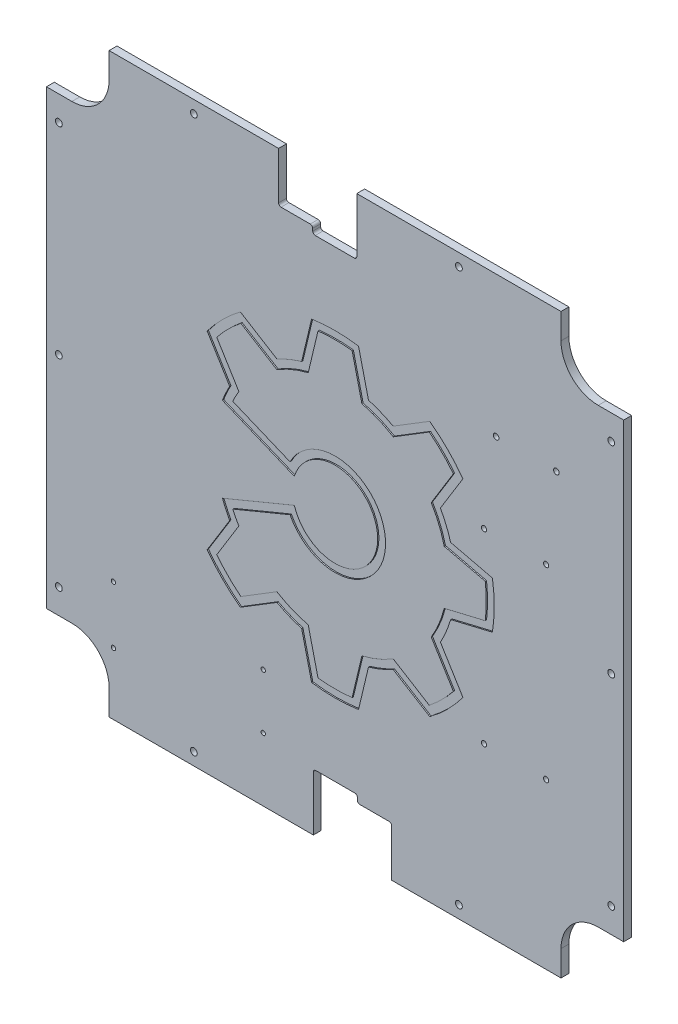
SolidWorks part; units mm, degrees
material "Acrylic (Medium-high impact)"
ref_plane "Front Plane" through (0, 0, 0) normal (0, 0, 1) x (1, 0, 0)
ref_plane "Top Plane" through (0, 0, 0) normal (0, 1, 0) x (1, 0, 0)
ref_plane "Right Plane" through (0, 0, 0) normal (1, 0, 0) x (0, 0, -1)
sketch "Sketch1" plane through (0, 0, 0) normal (0, 0, 1) x (1, 0, 0)
  line L0 (182, -212) -> (212, -212)
  line L1 (-182, -232.5) -> (-17.5, -232.5)
  line L2 (-232.5, -182) -> (-232.5, 0)
  line L3 (212, -212) -> (212, -182)
  line L4 (232.5, -182) -> (232.5, 0)
  line L5 (45.5, -232.5) -> (182, -232.5)
  line L6 (-232.5, 0) -> (232.5, 0) construction
  line L7 (-182, -212) -> (-212, -212)
  line L8 (-212, -212) -> (-212, -182)
  line L9 (232.5, 182) -> (232.5, 0)
  line L10 (232.5, 182) -> (212, 182)
  line L11 (212, 212) -> (212, 182)
  line L12 (182, 212) -> (212, 212)
  line L13 (182, 232.5) -> (182, 212)
  line L14 (182, 232.5) -> (17.5, 232.5)
  line L15 (17.5, 232.5) -> (17.5, 186.5)
  line L16 (-45.5, 186.5) -> (17.5, 186.5)
  line L17 (-45.5, 232.5) -> (-45.5, 186.5)
  line L18 (-45.5, 232.5) -> (-182, 232.5)
  line L19 (-182, 232.5) -> (-182, 212)
  line L20 (-182, 212) -> (-212, 212)
  line L21 (232.5, -182) -> (212, -182)
  line L22 (182, -232.5) -> (182, -212)
  line L23 (-212, 212) -> (-212, 182)
  line L24 (45.5, -232.5) -> (45.5, -186.5)
  line L25 (45.5, -186.5) -> (-17.5, -186.5)
  line L26 (-17.5, -232.5) -> (-17.5, -186.5)
  line L27 (-232.5, 182) -> (-212, 182)
  line L28 (-232.5, 182) -> (-232.5, 0)
  line L29 (-232.5, -182) -> (-212, -182)
  line L30 (-182, -232.5) -> (-182, -212)
  line L31 (0, 0) -> (0, -232.5) construction
  line L32 (-116.5, 222.5) -> (102.5, 222.5) construction
  circle A0 centre (-222.5, -162) radius 2.75
  circle A1 centre (222.5, -162) radius 2.75
  circle A2 centre (222.5, 162) radius 2.75
  circle A3 centre (-222.5, 162) radius 2.75
  circle A4 centre (-222.5, 0) radius 2.75
  circle A5 centre (222.5, 0) radius 2.75
  circle A6 centre (-113.75, 222.5) radius 2.75
  circle A7 centre (99.75, 222.5) radius 2.75
  circle A8 centre (99.75, -222.5) radius 2.75
  circle A9 centre (-113.75, -222.5) radius 2.75
  point P0 (0, 0)
  point P3 (0, 0)
  point P38 (0, 0)
  point P40 (14, -186.5)
  point P55 (-113.75, 232.5)
  point P56 (99.75, 232.5)
  point P68 (0, 0)
  dimension "D21" = 20.5
  dimension "D22" = 20.5
  dimension "D23" = 232.5
  dimension "D7" = 5.5
  dimension "D8" = 10
  dimension "D9" = 20
  dimension "D13" = 10
  dimension "D3" = 50.5
  dimension "D4" = 20.5
  dimension "D5" = 20.5
  dimension "D6" = 2
  dimension "D10" = 14
  dimension "D11" = 50.5
  dimension "D12" = 50.5
  dimension "D15" = 63
  dimension "D16" = 46
  dimension "D18" = 50.5
  dimension "D20" = 465
extrude "Boss-Extrude1" add sketch "Sketch1" along normal blind 6.35
sketch "Sketch4" plane through (0, 0, 6.35) normal (0, 0, 1) x (1, 0, 0)
  line L1 (45.5, -186.5) -> (18, -186.5)
  line L2 (45.5, -186.5) -> (45.5, -192.5)
  line L3 (45.5, -192.5) -> (18, -192.5)
  line L4 (18, -186.5) -> (18, -192.5)
  line L5 (-45.5, 186.5) -> (-18, 186.5)
  line L6 (-45.5, 186.5) -> (-45.5, 192.5)
  line L7 (-45.5, 192.5) -> (-18, 192.5)
  line L8 (-18, 186.5) -> (-18, 192.5)
  dimension "D1" = 27.5
  dimension "D2" = 6
extrude "Boss-Extrude2" add sketch "Sketch4" against normal up to surface (6.35 mm away) up to face at (0, 0, 0)
sketch "Sketch2" plane through (0, 0, 6.35) normal (0, 0, 1) x (1, 0, 0)
  line L0 (232.5, 182) -> (212, 182) construction
  line L1 (212, 212) -> (182, 212) construction
  line L2 (212, 182) -> (212, 212) construction
  line L3 (212, 212) -> (182, 212)
  line L4 (212, 182) -> (212, 212)
  line L5 (182, -212) -> (212, -212) construction
  line L6 (212, -212) -> (212, -182) construction
  line L7 (182, -212) -> (212, -212)
  line L8 (212, -212) -> (212, -182)
  line L9 (-212, -212) -> (-182, -212) construction
  line L10 (-212, -182) -> (-212, -212) construction
  line L11 (-212, 212) -> (-212, 182) construction
  line L12 (-182, 212) -> (-212, 212) construction
  line L13 (-212, -212) -> (-182, -212)
  line L14 (-212, -182) -> (-212, -212)
  line L15 (-212, 212) -> (-212, 182)
  line L16 (-182, 212) -> (-212, 212)
  arc A0 (182, 212) -> (212, 182) centre (212, 212) ccw
  arc A1 (212, -182) -> (182, -212) centre (212, -212) ccw
  arc A2 (-212, 182) -> (-182, 212) centre (-212, 212) ccw
  arc A3 (-182, -212) -> (-212, -182) centre (-212, -212) ccw
extrude "Cut-Extrude1" cut sketch "Sketch2" against normal up to surface (6.35 mm away) contours A0 L4 L3
sketch "Sketch3" plane through (0, 0, 6.35) normal (0, 0, 1) x (1, 0, 0)
  line L0 (0, 0) -> (125, 0) construction
  line L1 (0, 0) -> (123.9306, -16.3158) construction
  line L2 (0, 0) -> (115.4849, -47.8354) construction
  line L3 (0, 0) -> (120.7407, -32.3524) construction
  line L4 (123.9306, -16.3158) -> (90.5555, -24.2643) construction
  line L5 (123.9306, 16.3158) -> (90.5555, 24.2643) construction
  line L6 (76.0952, -99.1692) -> (46.875, -81.1899) construction
  line L7 (99.1692, -76.0952) -> (81.1899, -46.875) construction
  line L8 (-16.3158, -123.9306) -> (-24.2643, -90.5555) construction
  line L9 (16.3158, -123.9306) -> (24.2643, -90.5555) construction
  line L10 (-99.1692, -76.0952) -> (-81.1899, -46.875) construction
  line L11 (-76.0952, -99.1692) -> (-46.875, -81.1899) construction
  line L12 (-82.4139, 37.5736) -> (-36.2491, 18.4515)
  line L13 (-95.3084, 75.8792) -> (-77.4822, 46.9078)
  line L14 (-76.0952, 99.1692) -> (-46.875, 81.1899) construction
  line L15 (-99.1692, 76.0952) -> (-81.1899, 46.875) construction
  line L16 (16.3158, 123.9306) -> (24.2643, 90.5555) construction
  line L17 (-16.3158, 123.9306) -> (-24.2643, 90.5555) construction
  line L18 (99.1692, 76.0952) -> (81.1899, 46.875) construction
  line L19 (76.0952, 99.1692) -> (46.875, 81.1899) construction
  line L20 (0, 0) -> (88.3883, -88.3883) construction
  line L21 (0, 0) -> (0, -125) construction
  line L22 (0, 0) -> (-88.3883, -88.3883) construction
  line L23 (0, 0) -> (-125, 0) construction
  line L24 (0, 0) -> (-88.3883, 88.3883) construction
  line L25 (0, 0) -> (0, 125) construction
  line L26 (0, 0) -> (88.3883, 88.3883) construction
  line L27 (-86.6137, 35.8766) -> (-34.6455, 14.3506) construction
  line L28 (-86.6137, -35.8766) -> (-34.6455, -14.3506) construction
  line L29 (-75.8792, 95.3084) -> (-46.9078, 77.4822)
  line L30 (-123.9306, 16.3158) -> (-90.5555, 24.2643) [skipped]
  line L31 (-123.9306, -16.3158) -> (-90.5555, -24.2643) [skipped]
  line L32 (-13.7385, 121.0479) -> (-21.6193, 87.957)
  line L33 (13.7385, 121.0479) -> (21.6193, 87.957)
  line L34 (75.8792, 95.3084) -> (46.9078, 77.4822)
  line L35 (95.3084, 75.8792) -> (77.4822, 46.9078)
  line L36 (121.0479, 13.7385) -> (87.957, 21.6193)
  line L37 (121.0479, -13.7385) -> (87.957, -21.6193)
  line L38 (95.3084, -75.8792) -> (77.4822, -46.9078)
  line L39 (75.8792, -95.3084) -> (46.9078, -77.4822)
  line L40 (13.7385, -121.0479) -> (21.6193, -87.957)
  line L41 (-13.7385, -121.0479) -> (-21.6193, -87.957)
  line L42 (-75.8792, -95.3084) -> (-46.9078, -77.4822)
  line L43 (-95.3084, -75.8792) -> (-77.4822, -46.9078)
  line L44 (-82.4139, -37.5736) -> (-36.2491, -18.4515)
  line L45 (-90.714, 34.1384) -> (-32.7912, 10.146)
  line L46 (-103.0085, 76.2763) -> (-84.8748, 46.8052)
  line L47 (-76.2763, 103.0085) -> (-46.8052, 84.8748)
  line L48 (-18.9025, 126.7735) -> (-26.9193, 93.1118)
  line L49 (18.9025, 126.7735) -> (26.9193, 93.1118)
  line L50 (76.2763, 103.0085) -> (46.8052, 84.8748)
  line L51 (103.0085, 76.2763) -> (84.8748, 46.8052)
  line L52 (126.7735, 18.9025) -> (93.1118, 26.9193)
  line L53 (126.7735, -18.9025) -> (93.1118, -26.9193)
  line L54 (103.0085, -76.2763) -> (84.8748, -46.8052)
  line L55 (76.2763, -103.0085) -> (46.8052, -84.8748)
  line L56 (18.9025, -126.7735) -> (26.9193, -93.1118)
  line L57 (-18.9025, -126.7735) -> (-26.9193, -93.1118)
  line L58 (-76.2763, -103.0085) -> (-46.8052, -84.8748)
  line L59 (-103.0085, -76.2763) -> (-84.8748, -46.8052)
  line L60 (-90.714, -34.1384) -> (-32.7912, -10.146)
  line L61 (55, 0) -> (-55, 0) construction
  arc A0 (-34.6455, -14.3506) -> (-34.6455, 14.3506) centre (0, 0) ccw construction
  arc A1 (99.1692, 76.0952) -> (76.0952, 99.1692) centre (0, 0) ccw construction
  arc A2 (-36.2491, -18.4515) -> (-36.2491, 18.4515) centre (0, 0) ccw
  arc A3 (90.5555, 24.2643) -> (81.1899, 46.875) centre (0, 0) ccw construction
  arc A4 (81.1899, -46.875) -> (90.5555, -24.2643) centre (0, 0) ccw construction
  arc A5 (24.2643, -90.5555) -> (46.875, -81.1899) centre (0, 0) ccw construction
  arc A6 (-46.875, -81.1899) -> (-24.2643, -90.5555) centre (0, 0) ccw construction
  arc A7 (-86.6137, -35.8766) -> (-81.1899, -46.875) centre (0, 0) ccw construction
  arc A8 (-81.1899, 46.875) -> (-86.6137, 35.8766) centre (0, 0) ccw construction
  arc A9 (-24.2643, 90.5555) -> (-46.875, 81.1899) centre (0, 0) ccw construction
  arc A10 (46.875, 81.1899) -> (24.2643, 90.5555) centre (0, 0) ccw construction
  arc A11 (115.4849, -47.8354) -> (120.7407, -32.3524) centre (0, 0) ccw construction
  arc A12 (123.9306, -16.3158) -> (123.9306, 16.3158) centre (0, 0) ccw construction
  arc A13 (76.0952, -99.1692) -> (99.1692, -76.0952) centre (0, 0) ccw construction
  arc A14 (-16.3158, -123.9306) -> (16.3158, -123.9306) centre (0, 0) ccw construction
  arc A15 (-99.1692, -76.0952) -> (-76.0952, -99.1692) centre (0, 0) ccw construction
  arc A16 (-77.4822, 46.9078) -> (-82.4139, 37.5736) centre (0, 0) ccw
  arc A17 (-76.0952, 99.1692) -> (-99.1692, 76.0952) centre (0, 0) ccw construction
  arc A18 (16.3158, 123.9306) -> (-16.3158, 123.9306) centre (0, 0) ccw construction
  arc A19 (-75.8792, 95.3084) -> (-95.3084, 75.8792) centre (0, 0) ccw
  arc A20 (-21.6193, 87.957) -> (-46.9078, 77.4822) centre (0, 0) ccw
  arc A21 (13.7385, 121.0479) -> (-13.7385, 121.0479) centre (0, 0) ccw
  arc A22 (46.9078, 77.4822) -> (21.6193, 87.957) centre (0, 0) ccw
  arc A23 (95.3084, 75.8792) -> (75.8792, 95.3084) centre (0, 0) ccw
  arc A24 (87.957, 21.6193) -> (77.4822, 46.9078) centre (0, 0) ccw
  arc A25 (121.0479, -13.7385) -> (121.0479, 13.7385) centre (0, 0) ccw
  arc A26 (77.4822, -46.9078) -> (87.957, -21.6193) centre (0, 0) ccw
  arc A27 (75.8792, -95.3084) -> (95.3084, -75.8792) centre (0, 0) ccw
  arc A28 (21.6193, -87.957) -> (46.9078, -77.4822) centre (0, 0) ccw
  arc A29 (-13.7385, -121.0479) -> (13.7385, -121.0479) centre (0, 0) ccw
  arc A30 (-46.9078, -77.4822) -> (-21.6193, -87.957) centre (0, 0) ccw
  arc A31 (-95.3084, -75.8792) -> (-75.8792, -95.3084) centre (0, 0) ccw
  arc A32 (-82.4139, -37.5736) -> (-77.4822, -46.9078) centre (0, 0) ccw
  arc A33 (-32.7912, -10.146) -> (-32.7912, 10.146) centre (0, 0) ccw
  arc A34 (-84.8748, 46.8052) -> (-90.714, 34.1384) centre (0, 0) ccw
  arc A35 (-76.2763, 103.0085) -> (-103.0085, 76.2763) centre (0, 0) ccw
  arc A36 (-26.9193, 93.1118) -> (-46.8052, 84.8748) centre (0, 0) ccw
  arc A37 (18.9025, 126.7735) -> (-18.9025, 126.7735) centre (0, 0) ccw
  arc A38 (46.8052, 84.8748) -> (26.9193, 93.1118) centre (0, 0) ccw
  arc A39 (103.0085, 76.2763) -> (76.2763, 103.0085) centre (0, 0) ccw
  arc A40 (93.1118, 26.9193) -> (84.8748, 46.8052) centre (0, 0) ccw
  arc A41 (126.7735, -18.9025) -> (126.7735, 18.9025) centre (0, 0) ccw
  arc A42 (84.8748, -46.8052) -> (93.1118, -26.9193) centre (0, 0) ccw
  arc A43 (76.2763, -103.0085) -> (103.0085, -76.2763) centre (0, 0) ccw
  arc A44 (26.9193, -93.1118) -> (46.8052, -84.8748) centre (0, 0) ccw
  arc A45 (-18.9025, -126.7735) -> (18.9025, -126.7735) centre (0, 0) ccw
  arc A46 (-46.8052, -84.8748) -> (-26.9193, -93.1118) centre (0, 0) ccw
  arc A47 (-103.0085, -76.2763) -> (-76.2763, -103.0085) centre (0, 0) ccw
  arc A48 (-90.714, -34.1384) -> (-84.8748, -46.8052) centre (0, 0) ccw
  point P44 (0, 0)
  dimension "D3" = 250
  dimension "D4" = 187.5
  dimension "D5" = 75
  dimension "D1" = 22.5
  dimension "D2" = 7.5
  dimension "D6" = 15
  dimension "D8" = 22.5
  dimension "D9" = 22.5
  dimension "D10" = 3.175
  dimension "D11" = 3.175
  dimension "D7" = 8
extrude "Cut-Extrude2" cut sketch "Sketch3" against normal blind 1
fillet "Fillet1" radius 2 8 edges at (17.5, 186.5, 3.175) (-18, 186.5, 3.175) (-18, 192.5, 3.175) (-45.5, 192.5, 3.175) (45.5, -192.5, 3.175) (18, -192.5, 3.175) (18, -186.5, 3.175) (-17.5, -186.5, 3.175)
sketch "Sketch5" plane through (0, 0, 0) normal (0, 0, -1) x (-1, 0, 0)
  line L0 (-177.25, 119) -> (-178.25, 119) construction
  arc A0 (-177.25, 116.75) -> (-177.25, 121.25) centre (-177.25, 119) ccw construction
  circle A1 centre (-129.75, 119) radius 2.25 construction
  circle A3 centre (57.83, -137.3) radius 1.75 construction
  circle A5 centre (178.5, -136.3) radius 1.75 construction
  arc A6 (-177.25, 116.75) -> (-177.25, 121.25) centre (-177.25, 119) ccw construction
  circle A7 centre (-129.75, 119) radius 2.25
  circle A9 centre (57.83, -137.3) radius 1.75
  circle A11 centre (178.5, -136.3) radius 1.75
  circle A12 centre (-178.25, 119) radius 2.25
  circle A13 centre (178.5, -182.5) radius 1.75 construction
  circle A14 centre (57.83, -181.5) radius 1.75 construction
  circle A15 centre (178.5, -182.5) radius 1.75
  circle A16 centre (57.83, -181.5) radius 1.75
  circle A17 centre (-170, 50) radius 2.1 construction
  circle A18 centre (-120, 50) radius 2.1 construction
  circle A19 centre (-170, -100) radius 2.1 construction
  circle A20 centre (-120, -100) radius 2.1 construction
  circle A21 centre (-170, 50) radius 2.1
  circle A22 centre (-120, 50) radius 2.1
  circle A23 centre (-170, -100) radius 2.1
  circle A24 centre (-120, -100) radius 2.1
  dimension "D1" = 1
extrude "Cut-Extrude3" cut sketch "Sketch5" against normal through all
equation "\"D4@Sketch3\"=.75*\"D3@Sketch3\""
equation "\"D5@Sketch3\"=.3*\"D3@Sketch3\""
equation "\"D2@Sketch3\"=\"D1@Sketch3\"/3"
equation "\"D6@Sketch3\"=\"D1@Sketch3\"*(2/3)"
